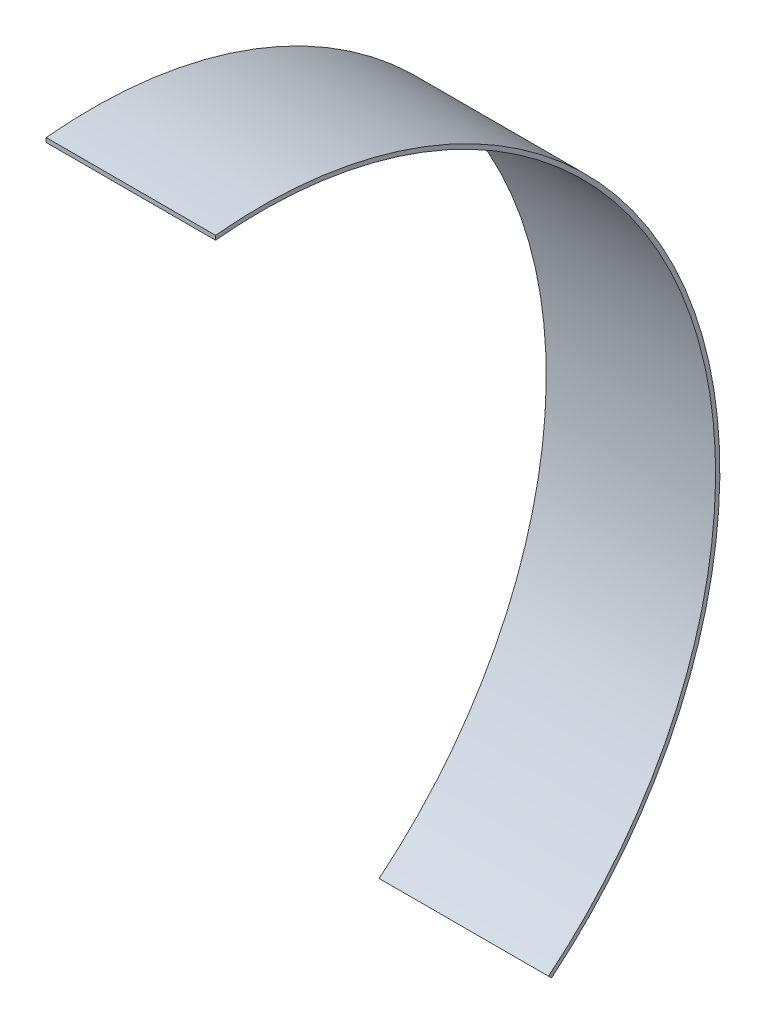
SolidWorks part; units mm, degrees
material "6061 Alloy"
ref_plane "Front Plane" through (0, 0, 0) normal (0, 0, 1) x (1, 0, 0)
ref_plane "Top Plane" through (0, 0, 0) normal (0, 1, 0) x (1, 0, 0)
ref_plane "Right Plane" through (0, 0, 0) normal (1, 0, 0) x (0, 0, -1)
sketch "Sketch1" plane through (0, 0, 0) normal (1, 0, 0) x (0, 0, -1)
  line L4 (0, 0) -> (0, 75) construction
  line L5 (0, 0) -> (53.033, -53.033) construction
  line L6 (-7.5, -3.1066) -> (47.4639, -58.0705)
  line L7 (-7.5, -3.1066) -> (-7.5, 74.6241)
  line L8 (-7.5, -3.1066) -> (-7.5, 95.6451) construction
  line L9 (0, 0) -> (0, 95.6451) construction
  line L10 (-7.5, -3.1066) -> (59.8943, -70.5009) construction
  line L11 (0, 0) -> (65.1976, -65.1976) construction
  circle A0 centre (0, 0) radius 75
  circle A1 centre (0, 0) radius 74.3
  point P5 (25, -70.7107)
  dimension "D1" = 150
  dimension "D2" = 0.7
  dimension "D3" = 135
  dimension "D4" = 7.5
  dimension "D5" = 25
extrude "Boss-Extrude1" add sketch "Sketch1" along normal mid plane 27.7 contours A1 L6 A0 L7
